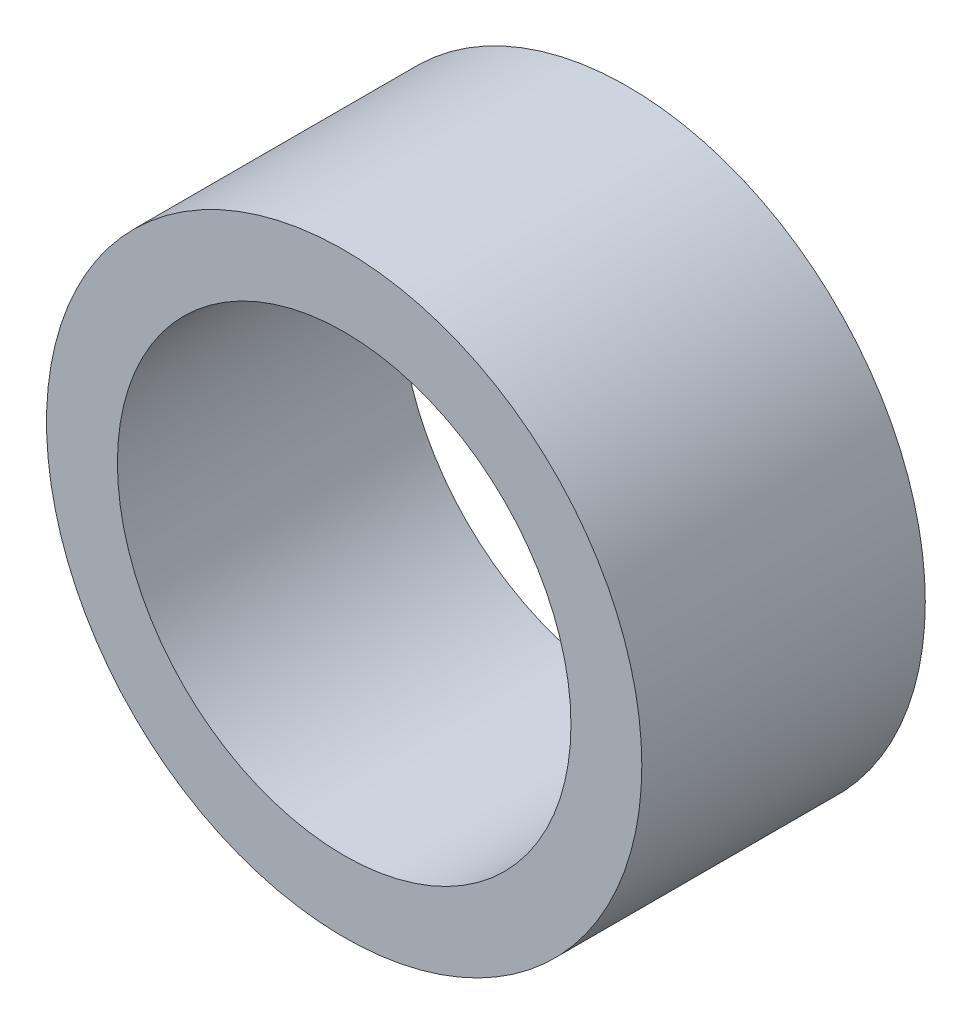
SolidWorks part; units mm, degrees
ref_plane "정면" through (0, 0, 0) normal (0, 0, 1) x (1, 0, 0)
ref_plane "윗면" through (0, 0, 0) normal (0, 1, 0) x (1, 0, 0)
ref_plane "우측면" through (0, 0, 0) normal (1, 0, 0) x (0, 0, -1)
sketch "스케치1" plane through (0, 0, 0) normal (0, 0, 1) x (1, 0, 0)
  circle A0 centre (0, 0) radius 4
  circle A1 centre (0, 0) radius 5.25
  dimension "D1" = 10.5
  dimension "D2" = 8
extrude "보스-돌출1" add sketch "스케치1" along normal blind 5 contours A1 A0
